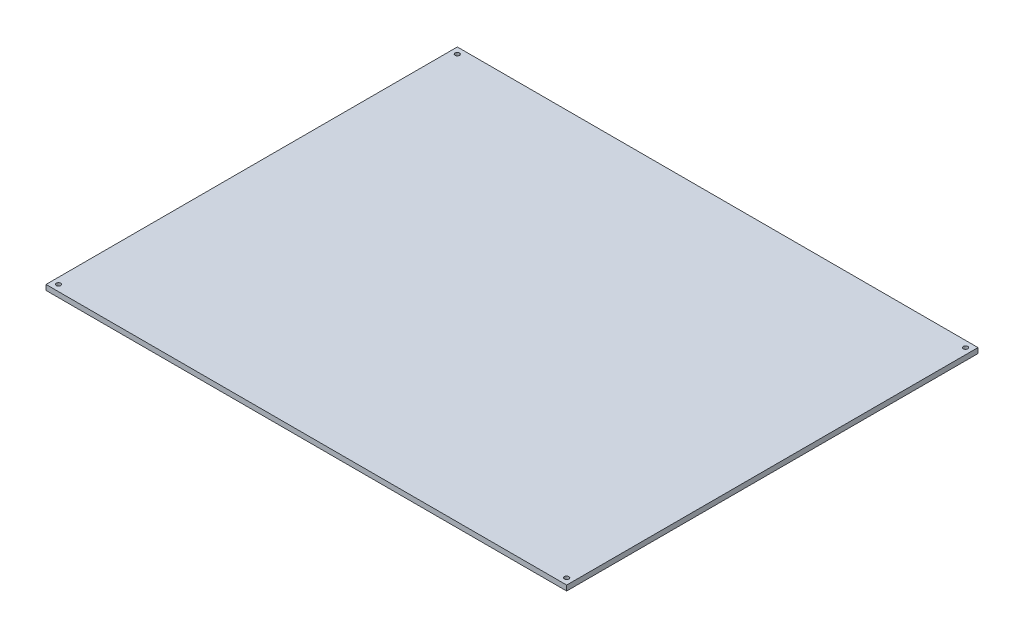
SolidWorks part; units mm, degrees
material "PVC rigide"
ref_plane "Face" through (0, 0, 0) normal (0, 0, 1) x (1, 0, 0)
ref_plane "Dessus" through (0, 0, 0) normal (0, 1, 0) x (1, 0, 0)
ref_plane "Droite" through (0, 0, 0) normal (1, 0, 0) x (0, 0, -1)
sketch "Esquisse1" plane through (0, 0, 0) normal (0, 1, 0) x (1, 0, 0)
  line L0 (-250, 0) -> (250, 0) construction
  line L1 (-250, 197.5) -> (250, 197.5)
  line L2 (-250, 197.5) -> (-250, -197.5)
  line L3 (-250, -197.5) -> (250, -197.5)
  line L4 (250, 197.5) -> (250, -197.5)
  dimension "D1" = 500
  dimension "D2" = 395
extrude "Boss.-Extru.1" add sketch "Esquisse1" along normal blind 5
sketch "Esquisse2" plane through (0, 5, 0) normal (0, 1, 0) x (1, 0, 0)
  line L0 (-250, 197.5) -> (-250, -197.5) construction
  line L1 (-250, -197.5) -> (250, -197.5) construction
  circle A0 centre (-244, -191.5) radius 2.1
  dimension "D1" = 4.2
  dimension "D2" = 6
  dimension "D3" = 6
extrude "Enlèv. mat.-Extru.1" cut sketch "Esquisse2" against normal through all
mirror "Symétrie1" about plane through (0, 0, 0) normal (1, 0, 0) of "Enlèv. mat.-Extru.1"
mirror "Symétrie2" about plane through (0, 0, 0) normal (0, 0, 1) of "Symétrie1", "Enlèv. mat.-Extru.1"
